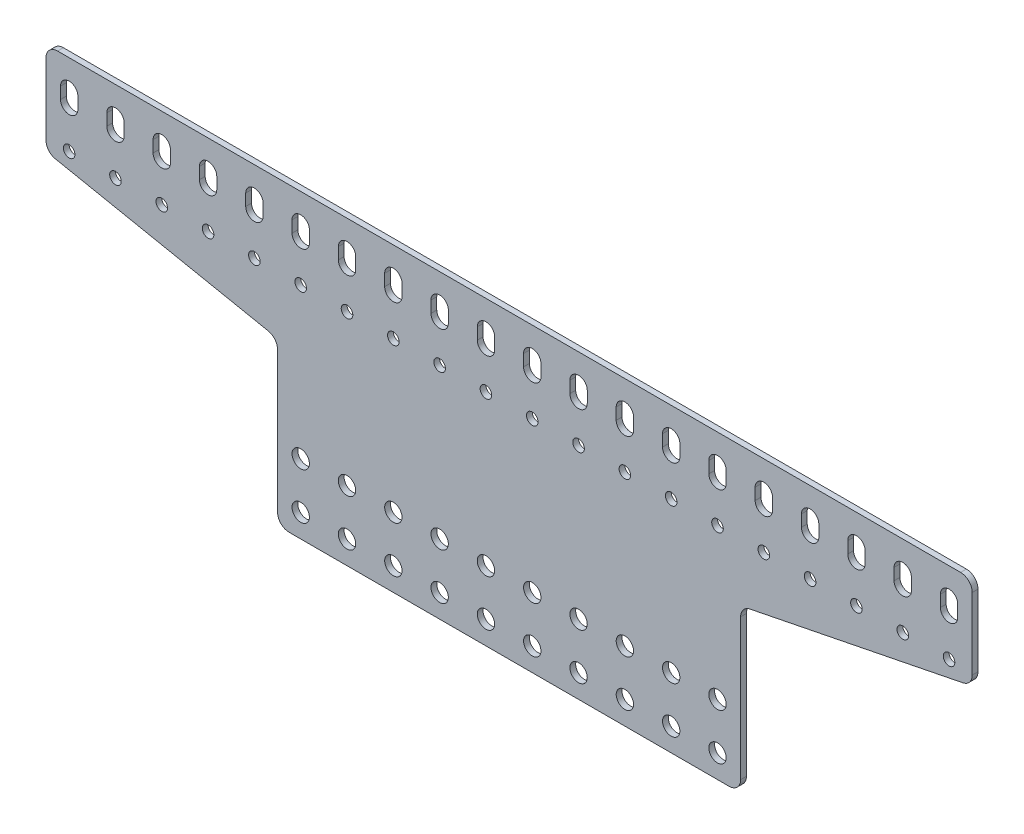
SolidWorks part; units mm, degrees
material "6061-T6 (SS)"
ref_plane "Front Plane" through (0, 0, 0) normal (0, 0, 1) x (1, 0, 0)
ref_plane "Top Plane" through (0, 0, 0) normal (0, 1, 0) x (1, 0, 0)
ref_plane "Right Plane" through (0, 0, 0) normal (1, 0, 0) x (0, 0, -1)
sketch "Sketch1" plane through (0, 0, 0) normal (0, 0, 1) x (1, 0, 0)
  line L0 (127, 82.55) -> (254, 82.55)
  line L1 (127, -82.55) -> (-127, -82.55)
  line L2 (127, -82.55) -> (127, 6.35)
  line L3 (127, 82.55) -> (-127, 82.55)
  line L4 (-127, -82.55) -> (-127, 6.35)
  line L5 (127, -82.55) -> (-127, 82.55) construction
  line L6 (127, 82.55) -> (-127, -82.55) construction
  line L7 (254, 82.55) -> (254, 31.75)
  line L8 (254, 31.75) -> (127, 6.35)
  line L9 (-127, 82.55) -> (-254, 82.55)
  line L10 (-254, 82.55) -> (-254, 31.75)
  line L11 (-254, 31.75) -> (-127, 6.35)
  line L12 (-241.3, 66.675) -> (-241.3, 60.325) construction
  line L13 (-127, -31.75) -> (127, -31.75) construction
  line L14 (114.3, -44.45) -> (88.9, -44.45) construction
  line L15 (-236.5375, 66.675) -> (-236.5375, 60.325)
  line L16 (-246.0625, 66.675) -> (-246.0625, 60.325)
  line L17 (-215.9, 66.675) -> (-215.9, 60.325) construction
  line L18 (-211.1375, 66.675) -> (-211.1375, 60.325)
  line L19 (-220.6625, 66.675) -> (-220.6625, 60.325)
  line L20 (-190.5, 66.675) -> (-190.5, 60.325) construction
  line L21 (-185.7375, 66.675) -> (-185.7375, 60.325)
  line L22 (-195.2625, 66.675) -> (-195.2625, 60.325)
  line L23 (-165.1, 66.675) -> (-165.1, 60.325) construction
  line L24 (-160.3375, 66.675) -> (-160.3375, 60.325)
  line L25 (-169.8625, 66.675) -> (-169.8625, 60.325)
  line L26 (-139.7, 66.675) -> (-139.7, 60.325) construction
  line L27 (-134.9375, 66.675) -> (-134.9375, 60.325)
  line L28 (-144.4625, 66.675) -> (-144.4625, 60.325)
  line L29 (-114.3, 66.675) -> (-114.3, 60.325) construction
  line L30 (-109.5375, 66.675) -> (-109.5375, 60.325)
  line L31 (-119.0625, 66.675) -> (-119.0625, 60.325)
  line L32 (-88.9, 66.675) -> (-88.9, 60.325) construction
  line L33 (-84.1375, 66.675) -> (-84.1375, 60.325)
  line L34 (-93.6625, 66.675) -> (-93.6625, 60.325)
  line L35 (-63.5, 66.675) -> (-63.5, 60.325) construction
  line L36 (-58.7375, 66.675) -> (-58.7375, 60.325)
  line L37 (-68.2625, 66.675) -> (-68.2625, 60.325)
  line L38 (-38.1, 66.675) -> (-38.1, 60.325) construction
  line L39 (-33.3375, 66.675) -> (-33.3375, 60.325)
  line L40 (-42.8625, 66.675) -> (-42.8625, 60.325)
  line L41 (-12.7, 66.675) -> (-12.7, 60.325) construction
  line L42 (-7.9375, 66.675) -> (-7.9375, 60.325)
  line L43 (-17.4625, 66.675) -> (-17.4625, 60.325)
  line L44 (12.7, 66.675) -> (12.7, 60.325) construction
  line L45 (17.4625, 66.675) -> (17.4625, 60.325)
  line L46 (7.9375, 66.675) -> (7.9375, 60.325)
  line L47 (38.1, 66.675) -> (38.1, 60.325) construction
  line L48 (42.8625, 66.675) -> (42.8625, 60.325)
  line L49 (33.3375, 66.675) -> (33.3375, 60.325)
  line L50 (63.5, 66.675) -> (63.5, 60.325) construction
  line L51 (68.2625, 66.675) -> (68.2625, 60.325)
  line L52 (58.7375, 66.675) -> (58.7375, 60.325)
  line L53 (88.9, 66.675) -> (88.9, 60.325) construction
  line L54 (93.6625, 66.675) -> (93.6625, 60.325)
  line L55 (84.1375, 66.675) -> (84.1375, 60.325)
  line L56 (114.3, 66.675) -> (114.3, 60.325) construction
  line L57 (119.0625, 66.675) -> (119.0625, 60.325)
  line L58 (109.5375, 66.675) -> (109.5375, 60.325)
  line L59 (139.7, 66.675) -> (139.7, 60.325) construction
  line L60 (144.4625, 66.675) -> (144.4625, 60.325)
  line L61 (134.9375, 66.675) -> (134.9375, 60.325)
  line L62 (165.1, 66.675) -> (165.1, 60.325) construction
  line L63 (169.8625, 66.675) -> (169.8625, 60.325)
  line L64 (160.3375, 66.675) -> (160.3375, 60.325)
  line L65 (190.5, 66.675) -> (190.5, 60.325) construction
  line L66 (195.2625, 66.675) -> (195.2625, 60.325)
  line L67 (185.7375, 66.675) -> (185.7375, 60.325)
  line L68 (215.9, 66.675) -> (215.9, 60.325) construction
  line L69 (220.6625, 66.675) -> (220.6625, 60.325)
  line L70 (211.1375, 66.675) -> (211.1375, 60.325)
  line L71 (241.3, 66.675) -> (241.3, 60.325) construction
  line L72 (246.0625, 66.675) -> (246.0625, 60.325)
  line L73 (236.5375, 66.675) -> (236.5375, 60.325)
  line L74 (-241.3, 38.1) -> (-215.9, 38.1) construction
  line L75 (0, 82.55) -> (0, -82.55) construction
  arc A0 (-236.5375, 66.675) -> (-246.0625, 66.675) centre (-241.3, 66.675) ccw
  arc A1 (-246.0625, 60.325) -> (-236.5375, 60.325) centre (-241.3, 60.325) ccw
  circle A2 centre (-241.3, 38.1) radius 3.175
  circle A3 centre (-215.9, 38.1) radius 3.175
  arc A4 (-211.1375, 66.675) -> (-220.6625, 66.675) centre (-215.9, 66.675) ccw
  arc A5 (-220.6625, 60.325) -> (-211.1375, 60.325) centre (-215.9, 60.325) ccw
  circle A6 centre (-190.5, 38.1) radius 3.175
  arc A7 (-185.7375, 66.675) -> (-195.2625, 66.675) centre (-190.5, 66.675) ccw
  arc A8 (-195.2625, 60.325) -> (-185.7375, 60.325) centre (-190.5, 60.325) ccw
  circle A9 centre (-165.1, 38.1) radius 3.175
  arc A10 (-160.3375, 66.675) -> (-169.8625, 66.675) centre (-165.1, 66.675) ccw
  arc A11 (-169.8625, 60.325) -> (-160.3375, 60.325) centre (-165.1, 60.325) ccw
  circle A12 centre (-139.7, 38.1) radius 3.175
  arc A13 (-134.9375, 66.675) -> (-144.4625, 66.675) centre (-139.7, 66.675) ccw
  arc A14 (-144.4625, 60.325) -> (-134.9375, 60.325) centre (-139.7, 60.325) ccw
  circle A15 centre (-114.3, 38.1) radius 3.175
  arc A16 (-109.5375, 66.675) -> (-119.0625, 66.675) centre (-114.3, 66.675) ccw
  arc A17 (-119.0625, 60.325) -> (-109.5375, 60.325) centre (-114.3, 60.325) ccw
  circle A18 centre (-88.9, 38.1) radius 3.175
  arc A19 (-84.1375, 66.675) -> (-93.6625, 66.675) centre (-88.9, 66.675) ccw
  arc A20 (-93.6625, 60.325) -> (-84.1375, 60.325) centre (-88.9, 60.325) ccw
  circle A21 centre (-63.5, 38.1) radius 3.175
  arc A22 (-58.7375, 66.675) -> (-68.2625, 66.675) centre (-63.5, 66.675) ccw
  arc A23 (-68.2625, 60.325) -> (-58.7375, 60.325) centre (-63.5, 60.325) ccw
  circle A24 centre (-38.1, 38.1) radius 3.175
  arc A25 (-33.3375, 66.675) -> (-42.8625, 66.675) centre (-38.1, 66.675) ccw
  arc A26 (-42.8625, 60.325) -> (-33.3375, 60.325) centre (-38.1, 60.325) ccw
  circle A27 centre (-12.7, 38.1) radius 3.175
  arc A28 (-7.9375, 66.675) -> (-17.4625, 66.675) centre (-12.7, 66.675) ccw
  arc A29 (-17.4625, 60.325) -> (-7.9375, 60.325) centre (-12.7, 60.325) ccw
  circle A30 centre (12.7, 38.1) radius 3.175
  arc A31 (17.4625, 66.675) -> (7.9375, 66.675) centre (12.7, 66.675) ccw
  arc A32 (7.9375, 60.325) -> (17.4625, 60.325) centre (12.7, 60.325) ccw
  circle A33 centre (38.1, 38.1) radius 3.175
  arc A34 (42.8625, 66.675) -> (33.3375, 66.675) centre (38.1, 66.675) ccw
  arc A35 (33.3375, 60.325) -> (42.8625, 60.325) centre (38.1, 60.325) ccw
  circle A36 centre (63.5, 38.1) radius 3.175
  arc A37 (68.2625, 66.675) -> (58.7375, 66.675) centre (63.5, 66.675) ccw
  arc A38 (58.7375, 60.325) -> (68.2625, 60.325) centre (63.5, 60.325) ccw
  circle A39 centre (88.9, 38.1) radius 3.175
  arc A40 (93.6625, 66.675) -> (84.1375, 66.675) centre (88.9, 66.675) ccw
  arc A41 (84.1375, 60.325) -> (93.6625, 60.325) centre (88.9, 60.325) ccw
  circle A42 centre (114.3, -44.45) radius 4.7625
  circle A43 centre (114.3, -69.85) radius 4.7625
  circle A44 centre (88.9, -44.45) radius 4.7625
  circle A45 centre (88.9, -69.85) radius 4.7625
  circle A46 centre (63.5, -44.45) radius 4.7625
  circle A47 centre (63.5, -69.85) radius 4.7625
  circle A48 centre (38.1, -44.45) radius 4.7625
  circle A49 centre (38.1, -69.85) radius 4.7625
  circle A50 centre (12.7, -44.45) radius 4.7625
  circle A51 centre (12.7, -69.85) radius 4.7625
  circle A52 centre (-12.7, -44.45) radius 4.7625
  circle A53 centre (-12.7, -69.85) radius 4.7625
  circle A54 centre (-38.1, -44.45) radius 4.7625
  circle A55 centre (-38.1, -69.85) radius 4.7625
  circle A56 centre (-63.5, -44.45) radius 4.7625
  circle A57 centre (-63.5, -69.85) radius 4.7625
  circle A58 centre (-88.9, -44.45) radius 4.7625
  circle A59 centre (-88.9, -69.85) radius 4.7625
  circle A60 centre (-114.3, -44.45) radius 4.7625
  circle A61 centre (-114.3, -69.85) radius 4.7625
  circle A63 centre (114.3, 38.1) radius 3.175
  arc A65 (119.0625, 66.675) -> (109.5375, 66.675) centre (114.3, 66.675) ccw
  arc A67 (109.5375, 60.325) -> (119.0625, 60.325) centre (114.3, 60.325) ccw
  circle A69 centre (139.7, 38.1) radius 3.175
  arc A71 (144.4625, 66.675) -> (134.9375, 66.675) centre (139.7, 66.675) ccw
  arc A73 (134.9375, 60.325) -> (144.4625, 60.325) centre (139.7, 60.325) ccw
  circle A75 centre (165.1, 38.1) radius 3.175
  arc A77 (169.8625, 66.675) -> (160.3375, 66.675) centre (165.1, 66.675) ccw
  arc A79 (160.3375, 60.325) -> (169.8625, 60.325) centre (165.1, 60.325) ccw
  circle A81 centre (190.5, 38.1) radius 3.175
  arc A83 (195.2625, 66.675) -> (185.7375, 66.675) centre (190.5, 66.675) ccw
  arc A85 (185.7375, 60.325) -> (195.2625, 60.325) centre (190.5, 60.325) ccw
  circle A87 centre (215.9, 38.1) radius 3.175
  arc A89 (220.6625, 66.675) -> (211.1375, 66.675) centre (215.9, 66.675) ccw
  arc A91 (211.1375, 60.325) -> (220.6625, 60.325) centre (215.9, 60.325) ccw
  circle A93 centre (241.3, 38.1) radius 3.175
  arc A95 (246.0625, 66.675) -> (236.5375, 66.675) centre (241.3, 66.675) ccw
  arc A97 (236.5375, 60.325) -> (246.0625, 60.325) centre (241.3, 60.325) ccw
  point P0 (0, 0)
  point P14 (-241.3, 63.5)
  point P26 (-215.9, 63.5)
  point P35 (-190.5, 63.5)
  point P44 (-165.1, 63.5)
  point P53 (-139.7, 63.5)
  point P62 (-114.3, 63.5)
  point P71 (-88.9, 63.5)
  point P80 (-63.5, 63.5)
  point P89 (-38.1, 63.5)
  point P98 (-12.7, 63.5)
  point P158 (12.7, 63.5)
  point P177 (38.1, 63.5)
  point P194 (63.5, 63.5)
  point P213 (88.9, 63.5)
  point P224 (114.3, 63.5)
  point P233 (139.7, 63.5)
  point P242 (165.1, 63.5)
  point P251 (190.5, 63.5)
  point P260 (215.9, 63.5)
  point P269 (241.3, 63.5)
  dimension "D4" = 12.7
  dimension "D3" = 146.05
  dimension "D14" = 9.525
  dimension "D8" = 4.7625
  dimension "D10" = 6.35
  dimension "D1" = 254
  dimension "D2" = 165.1
  dimension "D5" = 6.35
  dimension "D6" = 50.8
  dimension "D7" = 127
  dimension "D9" = 25.4
  dimension "D13" = 25.4
  dimension "D15" = 12.7
  dimension "D11" = 88.9
  dimension "D12" = 50.8
  dimension "D16" = 12.7
  dimension "D18" = 25.4
  dimension "D20" = 25.4
  dimension "D17" = 10
  dimension "D19" = 20
extrude "Boss-Extrude1" add sketch "Sketch1" along normal mid plane 3.175
fillet "Fillet1" radius 6.35 8 edges at (-127, 6.35, 0) (-127, -82.55, 0) (127, -82.55, 0) (127, 6.35, 0) (254, 31.75, 0) (254, 82.55, 0) (-254, 31.75, 0) (-254, 82.55, 0)
